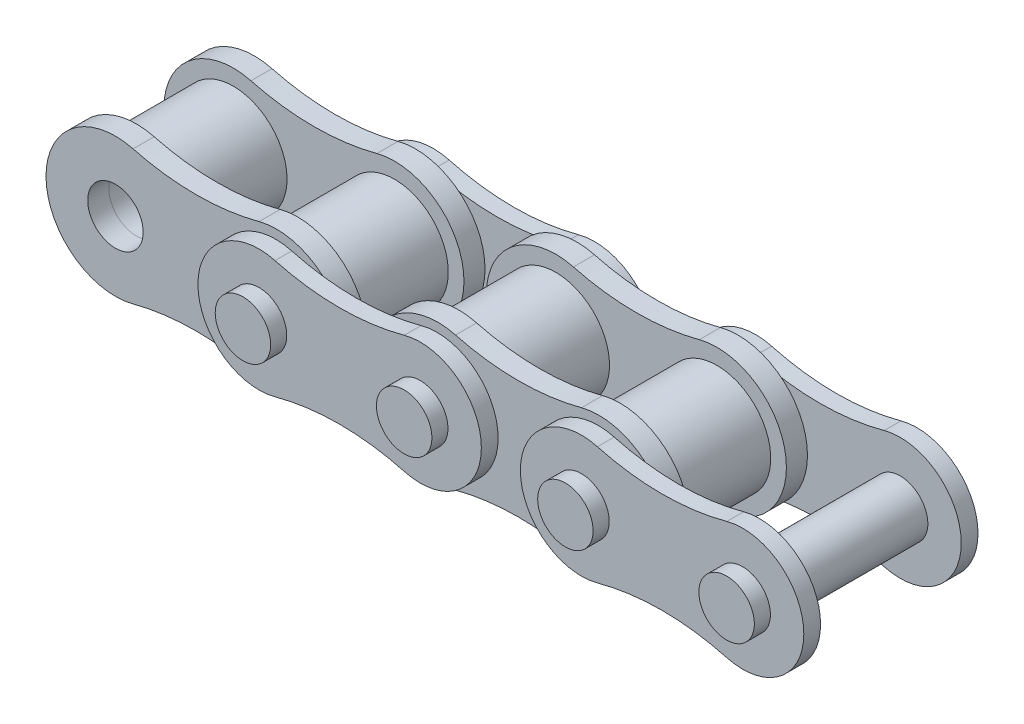
SolidWorks part; units mm, degrees
ref_plane "Front Plane" through (0, 0, 0) normal (0, 0, 1) x (1, 0, 0)
ref_plane "Top Plane" through (0, 0, 0) normal (0, 1, 0) x (1, 0, 0)
ref_plane "Right Plane" through (0, 0, 0) normal (1, 0, 0) x (0, 0, -1)
sketch "Sketch1" plane through (0, 0, 0) normal (0, 0, 1) x (1, 0, 0)
  line L0 (-4.7625, 0) -> (4.7625, 0) construction
  line L1 (-4.7625, 4.1021) -> (-4.7625, -4.1021) construction
  line L2 (0, -3.4868) -> (0, 3.4868) construction
  circle A0 centre (-4.7625, 0) radius 3.175
  circle A1 centre (4.7625, 0) radius 3.175
  circle A2 centre (-4.7625, 0) radius 1.6383
  circle A3 centre (4.7625, 0) radius 1.6383
  arc A4 (-3.7199, 3.9674) -> (-3.7199, -3.9674) centre (-4.7625, 0) ccw
  arc A5 (3.7199, -3.9674) -> (3.7199, 3.9674) centre (4.7625, 0) ccw
  arc A6 (-3.7199, 3.9674) -> (3.7199, 3.9674) centre (0, 18.1231) ccw
  arc A7 (-3.7199, -3.9674) -> (3.7199, -3.9674) centre (0, -18.1231) cw
  dimension "Roller Dia" = 6.35
  dimension "Pin Dia" = 3.2766
  dimension "Pitch" = 9.525
  dimension "H" = 8.2042
  dimension "D2" = 6.9736
sketch "Sketch2" plane through (0, 0, 0) normal (0, 1, 0) x (1, 0, 0)
  line L0 (0, 2.86) -> (0, -2.86) construction
  point P2 (0, -4.1046)
  point P4 (0, 4.1046)
  point P5 (0, 4.1554)
  point P6 (0, 5.146)
  dimension "W" = 5.72
  dimension "T" = 1.2446
  dimension "D1" = 1.2446
  dimension "T1" = 0.9906
  dimension "D3" = 0.0508
ref_plane "Plane1" through (0, 0, 2.86) normal (0, 0, 1) x (1, 0, 0)
ref_plane "Plane2" through (0, 0, -4.1554) normal (0, 0, 1) x (1, 0, 0)
sketch "Sketch4" plane through (0, 0, 0) normal (0, 0, 1) x (1, 0, 0)
  circle A0 centre (-4.7625, 0) radius 3.175 construction
  circle A1 centre (-4.7625, 0) radius 3.175
  circle A2 centre (4.7625, 0) radius 3.175 construction
  circle A3 centre (4.7625, 0) radius 3.175
  circle A4 centre (-4.7625, 0) radius 1.6637
  circle A5 centre (4.7625, 0) radius 1.6637
  dimension "D1" = 3.3274
  dimension "D2" = 3.3274
extrude "Boss-Extrude1" add sketch "Sketch4" along normal mid plane 5.72
sketch "Sketch5" plane through (0, 0, 2.86) normal (0, 0, 1) x (1, 0, 0)
  arc A0 (-3.7199, 3.9674) -> (-3.7199, -3.9674) centre (-4.7625, 0) ccw construction
  arc A1 (-3.7199, 3.9674) -> (3.7199, 3.9674) centre (0, 18.1231) ccw construction
  circle A2 centre (-4.7625, 0) radius 1.6383 construction
  arc A3 (3.7199, -3.9674) -> (3.7199, 3.9674) centre (4.7625, 0) ccw construction
  circle A4 centre (4.7625, 0) radius 1.6383 construction
  arc A5 (3.7199, -3.9674) -> (-3.7199, -3.9674) centre (0, -18.1231) ccw construction
  arc A6 (-3.7199, 3.9674) -> (-3.7199, -3.9674) centre (-4.7625, 0) ccw
  arc A7 (-3.7199, 3.9674) -> (3.7199, 3.9674) centre (0, 18.1231) ccw
  circle A8 centre (-4.7625, 0) radius 1.6383
  arc A9 (3.7199, -3.9674) -> (3.7199, 3.9674) centre (4.7625, 0) ccw
  circle A10 centre (4.7625, 0) radius 1.6383
  arc A11 (3.7199, -3.9674) -> (-3.7199, -3.9674) centre (0, -18.1231) ccw
extrude "Boss-Extrude2" add sketch "Sketch5" along normal up to vertex (1.2446 mm away) separate body up to point (0, 0, 4.1046)
pattern_linear "LPattern1" count 2 spacing 9.525 along (1, 0, 0) of bodies 102
sketch "Sketch7" plane through (0, 0, -4.1554) normal (0, 0, 1) x (1, 0, 0)
  line L0 (14.2875, 3.6098) -> (14.2875, -3.6098) construction
  arc A0 (5.7047, 3.4847) -> (5.7047, -3.4847) centre (4.7625, 0) ccw
  arc A1 (13.3453, -3.4847) -> (13.3453, 3.4847) centre (14.2875, 0) ccw
  arc A2 (3.7199, -3.9674) -> (3.7199, 3.9674) centre (4.7625, 0) ccw construction
  circle A3 centre (14.2875, 0) radius 3.175 construction
  arc A4 (5.7047, 3.4847) -> (13.3453, 3.4847) centre (9.525, 17.6136) ccw
  arc A5 (5.7047, -3.4847) -> (13.3453, -3.4847) centre (9.525, -17.6136) cw
  arc A6 (-3.7199, 3.9674) -> (3.7199, 3.9674) centre (0, 18.1231) ccw construction
  circle A7 centre (4.7625, 0) radius 1.6383 construction
  circle A8 centre (4.7625, 0) radius 1.6383
  circle A9 centre (14.2875, 0) radius 1.6383
  dimension "D2" = 7.2197
extrude "Boss-Extrude3" add sketch "Sketch7" against normal up to vertex (0.9906 mm away) separate body up to point (0, 0, -5.146)
mirror "Mirror1" about plane through (0, 0, 0) normal (0, 0, 1) of bodies 103 105
sketch "Sketch8" plane through (0, 0, 0) normal (0, 0, 1) x (1, 0, 0)
  circle A0 centre (4.7625, 0) radius 1.6383
  circle A1 centre (14.2875, 0) radius 1.6383
  circle A2 centre (4.7625, 0) radius 1.6383 construction
  circle A3 centre (14.2875, 0) radius 1.6383 construction
extrude "Boss-Extrude4" add sketch "Sketch8" against normal blind 6.096 and the other way blind 6.096 separate body
pattern_linear "LPattern2" count 2 spacing 19.05 along (1, 0, 0) of bodies 109 108 107 106 105 104 103 102 101
delete or keep bodies "Body-Delete1" type delete bodies bodies 115
combine bodies "Combine1" operation type add bodies to combine 102 103 104 105 106 107 108 109 110 111 112 113 114 116 117 118 101
sketch "Sketch9" plane through (0, 0, 0) normal (0, 0, 1) x (1, 0, 0)
  line L0 (33.3375, 3.6098) -> (33.3375, -3.6098) construction
  line L1 (23.8125, 4.1021) -> (23.8125, -4.1021) construction
  arc A0 (22.7699, -3.9674) -> (22.7699, 3.9674) centre (23.8125, 0) ccw construction
  arc A1 (23.8125, -4.1021) -> (23.8125, 4.1021) centre (23.8125, 0) ccw
  arc A2 (32.3953, -3.4847) -> (32.3953, 3.4847) centre (33.3375, 0) ccw construction
  arc A3 (33.3375, -3.6098) -> (33.3375, 3.6098) centre (33.3375, 0) ccw
  circle A4 centre (-4.7625, 0) radius 3.175 construction
  circle A5 centre (-4.7625, 0) radius 3.175
equation "\"D2@Sketch1\" =\"H@Sketch1\"*.85"
equation "\"D1@Sketch2\" = \"T@Sketch2\""
equation "\"D1@Sketch4\" = \"Pin Dia@Sketch1\"+.002"
equation "\"D2@Sketch4\" = \"D1@Sketch4\""
equation "\"D1@Boss-Extrude1\" = \"W@Sketch2\""
equation "\"D3@LPattern1\" = \"Pitch@Sketch1\""
equation "\"D3@LPattern2\" = \"Pitch@Sketch1\"*2"
equation "\"D2@Sketch7\" = \"H@Sketch1\"*.88"
